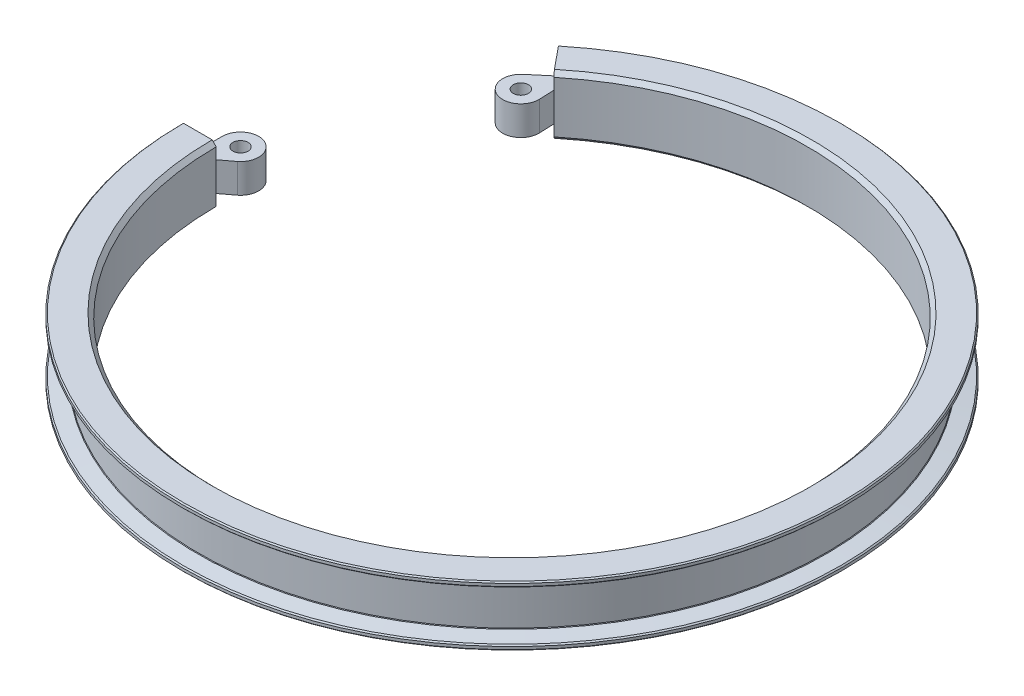
SolidWorks part; units mm, degrees
ref_plane "Front Plane" through (0, 0, 0) normal (0, 0, 1) x (1, 0, 0)
ref_plane "Top Plane" through (0, 0, 0) normal (0, 1, 0) x (1, 0, 0)
ref_plane "Right Plane" through (0, 0, 0) normal (1, 0, 0) x (0, 0, -1)
sketch "Sketch1" plane through (0, 0, 0) normal (0, 0, 1) x (1, 0, 0)
  line L1 (0, 0) -> (0, 15.6291) construction
  line L2 (-68.072, 4.699) -> (-68.072, -4.699)
  line L3 (-66.167, 0) -> (-66.167, -7.3462) construction
  line L4 (-68.1855, 4.826) -> (-71.374, 5.3882)
  line L5 (-71.374, 5.3882) -> (-71.628, 5.6422)
  line L6 (-71.628, 5.6422) -> (-71.628, 6.2332)
  line L7 (-71.628, 6.2332) -> (-71.374, 6.4872)
  line L8 (-71.374, 6.4872) -> (-65.1457, 6.4872)
  line L9 (-65.1457, 6.4872) -> (-64.262, 5.6035)
  line L10 (-64.262, 5.6035) -> (-64.262, -5.6035)
  line L11 (-68.1855, -4.826) -> (-71.374, -5.3882)
  line L12 (-71.374, -5.3882) -> (-71.628, -5.6422)
  line L13 (-65.1457, -6.4872) -> (-64.262, -5.6035)
  line L14 (-71.374, -6.4872) -> (-65.1457, -6.4872)
  line L15 (-71.628, -6.2332) -> (-71.374, -6.4872)
  line L16 (-71.628, -5.6422) -> (-71.628, -6.2332)
  line L17 (-66.167, 0) -> (7.6654, 0) construction
  line L18 (7.6654, 0) -> (-33.6575, 500000) construction
  arc A0 (-68.072, 4.699) -> (-68.1855, 4.826) centre (-68.3102, 4.6004) ccw
  arc A1 (-68.072, -4.699) -> (-68.1855, -4.826) centre (-68.3102, -4.6004) cw
  point P2 (-66.167, 6.4872)
  point P19 (-68.072, 0)
  point P24 (-64.262, 0)
  dimension "D6" = 3.302
  dimension "D3" = 64.262
  dimension "D4" = 66.167
  dimension "D7" = 3.81
  dimension "D9" = 45
  dimension "D10" = 0.254
  dimension "D11" = 0.254
sketch "Sketch4" plane through (0, 0, 0) normal (0, 1, 0) x (1, 0, 0)
  line L0 (0, 0) -> (-84.3208, 0) construction
  line L1 (0, 0) -> (-41.8732, 51.2319) construction
  arc A0 (-66.167, 0) -> (-41.8732, 51.2319) centre (0, 0) ccw
  dimension "D1" = 50.74
sweep "Sweep2" add profiles "Sketch1" path "Sketch4"
sketch "Sketch5" plane through (0, 0, 0) normal (0, 1, 0) x (1, 0, 0)
  line L0 (0, 0) -> (-71.374, 0) construction
  line L1 (-64.0609, 5.08) -> (-44.4699, 46.39) construction
  line L2 (-68.072, 0) -> (-67.9978, 5.0553)
  line L3 (-61.6341, 1.9799) -> (-64.262, 0)
  line L4 (-64.262, 0) -> (-68.072, 0)
  line L5 (-54.2654, 25.735) -> (0, 0) construction
  line L6 (-40.5338, 46.4725) -> (-40.6636, 49.7602)
  line L7 (-40.6636, 49.7602) -> (-43.0745, 52.7104)
  line L8 (-43.0745, 52.7104) -> (-46.942, 49.4541)
  line L9 (0, 0) -> (-43.0745, 52.7104) construction
  circle A0 centre (0, 0) radius 66.167 construction
  circle A1 centre (0, 0) radius 64.262 construction
  circle A2 centre (0, 0) radius 68.072 construction
  circle A3 centre (-64.0609, 5.08) radius 1.651
  arc A4 (-67.9978, 5.0553) -> (-61.6341, 1.9799) centre (-64.0609, 5.08) cw
  circle A5 centre (-44.4699, 46.39) radius 1.651
  arc A6 (-46.942, 49.4541) -> (-40.5338, 46.4725) centre (-44.4699, 46.39) ccw
  point P15 (-54.2654, 25.735)
  dimension "D1" = 132.334
  dimension "D2" = 128.524
  dimension "D3" = 3.302
  dimension "D6" = 2.286
  dimension "D8" = 136.144
  dimension "D4" = 5.08
  dimension "D5" = 45.72
  dimension "D7" = 50.745
extrude "Boss-Extrude2" add sketch "Sketch5" along normal blind 3.175 and the other way blind 3.175
